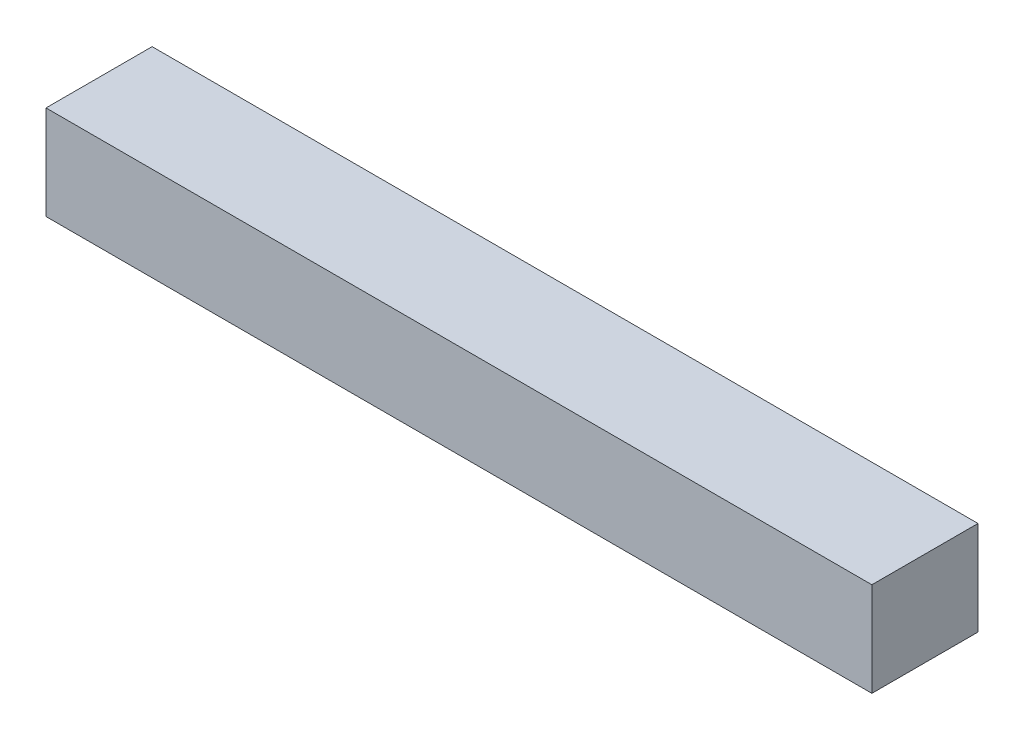
SolidWorks part; units mm, degrees
ref_plane "Front Plane" through (0, 0, 0) normal (0, 0, 1) x (1, 0, 0)
ref_plane "Top Plane" through (0, 0, 0) normal (0, 1, 0) x (1, 0, 0)
ref_plane "Right Plane" through (0, 0, 0) normal (1, 0, 0) x (0, 0, -1)
sketch "Sketch1" plane through (0, 0, 0) normal (0, 1, 0) x (1, 0, 0)
  line L1 (-10.5953, -5.5368) -> (75.0047, -5.5368)
  line L2 (-10.5953, -5.5368) -> (-10.5953, 5.4632)
  line L3 (-10.5953, 5.4632) -> (75.0047, 5.4632)
  line L4 (75.0047, -5.5368) -> (75.0047, 5.4632)
  dimension "D1" = 11
  dimension "D2" = 85.6
extrude "Boss-Extrude1" add sketch "Sketch1" along normal blind 9.75
